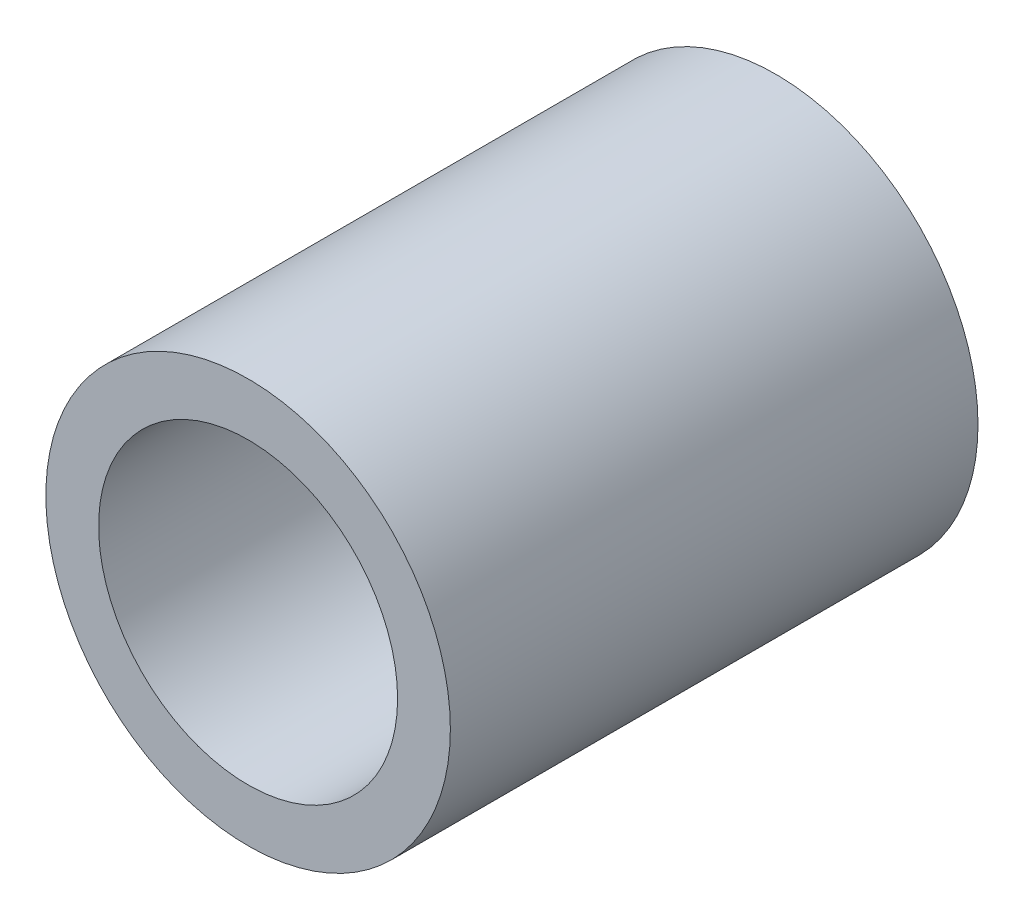
SolidWorks part; units mm, degrees
ref_plane "前视基准面" through (0, 0, 0) normal (0, 0, 1) x (1, 0, 0)
ref_plane "上视基准面" through (0, 0, 0) normal (0, 1, 0) x (1, 0, 0)
ref_plane "右视基准面" through (0, 0, 0) normal (1, 0, 0) x (0, 0, -1)
sketch "草图1" plane through (0, 0, 0) normal (0, 0, 1) x (1, 0, 0)
  circle A0 centre (0, 0) radius 2.55
  circle A1 centre (0, 0) radius 3.45
  dimension "D1" = 5.1
  dimension "D2" = 6.9
extrude "凸台-拉伸1" add sketch "草图1" along normal blind 9
